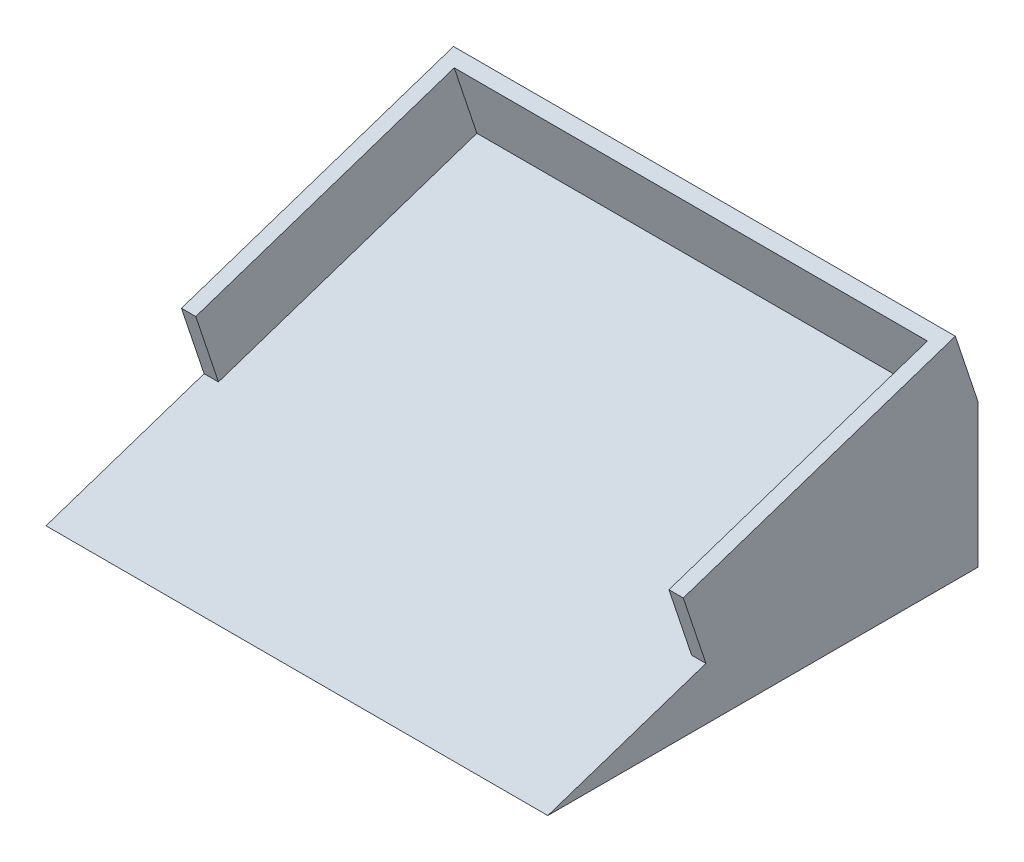
SolidWorks part; units mm, degrees
ref_plane "Front Plane" through (0, 0, 0) normal (0, 0, 1) x (1, 0, 0)
ref_plane "Top Plane" through (0, 0, 0) normal (0, 1, 0) x (1, 0, 0)
ref_plane "Right Plane" through (0, 0, 0) normal (1, 0, 0) x (0, 0, -1)
sketch "Sketch1" plane through (0, 0, 0) normal (0, 1, 0) x (1, 0, 0)
  line L1 (0, 0) -> (88.9, 0)
  line L2 (0, 0) -> (0, 76.2)
  line L3 (0, 76.2) -> (88.9, 76.2)
  line L4 (88.9, 0) -> (88.9, 76.2)
  dimension "D1" = 88.9
  dimension "D2" = 76.2
extrude "Boss-Extrude1" add sketch "Sketch1" along normal blind 25.4
sketch "Sketch2" plane through (88.9, 0, 0) normal (1, 0, 0) x (0, 0, -1)
  line L0 (76.2, 25.4) -> (0, 0)
  line L1 (0, 0) -> (0, 25.4)
  line L2 (0, 25.4) -> (76.2, 25.4)
extrude "Cut-Extrude1" cut sketch "Sketch2" against normal through all
sketch "Sketch3" plane through (0, 0, 0) normal (0, 0.9487, 0.3162) x (1, 0, 0)
  line L0 (0, 29.5219) -> (2.54, 29.5219)
  line L1 (0, 0) -> (0, 80.3219) construction
  line L2 (2.54, 29.5219) -> (2.54, 77.7819)
  line L3 (2.54, 77.7819) -> (86.36, 77.7819)
  line L4 (86.36, 77.7819) -> (86.36, 29.5219)
  line L5 (86.36, 29.5219) -> (88.9, 29.5219)
  line L6 (88.9, 0) -> (88.9, 80.3219) construction
  line L7 (88.9, 29.5219) -> (88.9, 80.3219)
  line L8 (88.9, 80.3219) -> (0, 80.3219)
  line L9 (0, 80.3219) -> (0, 29.5219)
  dimension "D1" = 2.54
  dimension "D2" = 2.54
  dimension "D3" = 50.8
extrude "Boss-Extrude2" add sketch "Sketch3" along normal blind 12.7
